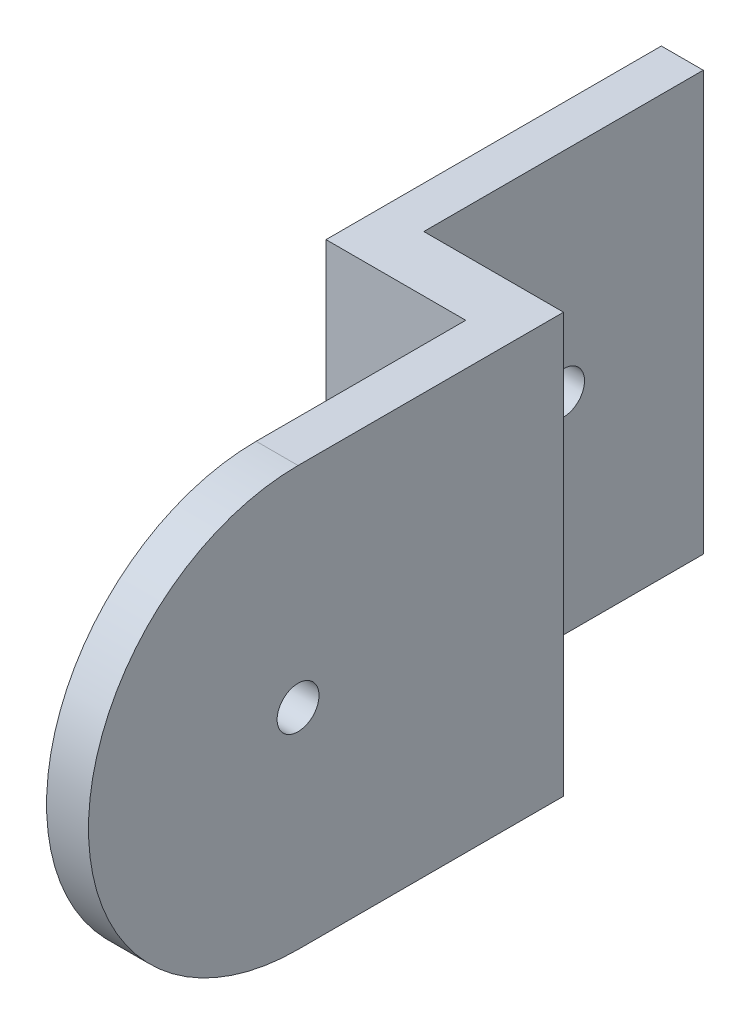
SolidWorks part; units mm, degrees
ref_plane "前视基准面" through (0, 0, 0) normal (0, 0, 1) x (1, 0, 0)
ref_plane "上视基准面" through (0, 0, 0) normal (0, 1, 0) x (1, 0, 0)
ref_plane "右视基准面" through (0, 0, 0) normal (1, 0, 0) x (0, 0, -1)
sketch "草图1" plane through (0, 0, 0) normal (0, 0, 1) x (1, 0, 0)
  line L1 (0, 0) -> (81, 0)
  line L2 (0, 0) -> (0, -30)
  line L3 (0, -30) -> (81, -30)
  line L4 (81, 0) -> (81, -30)
  dimension "D1" = 81
  dimension "D2" = 30
extrude "凸台-拉伸1" add sketch "草图1" along normal blind 4
sketch "草图2" plane through (0, 0, 0) normal (0, 0, -1) x (-1, 0, 0)
  line L0 (0, -30) -> (-81, -30) construction
  line L1 (0, 0) -> (-3, 0)
  line L2 (0, 0) -> (0, -30)
  line L3 (0, -30) -> (-3, -30)
  line L4 (-3, 0) -> (-3, -30)
  line L6 (-81, 0) -> (-78, 0)
  line L7 (-81, 0) -> (-81, -30)
  line L8 (-81, -30) -> (-78, -30)
  line L9 (-78, 0) -> (-78, -30)
  dimension "D1" = 3
  dimension "D2" = 3
extrude "凸台-拉伸2" add sketch "草图2" along normal blind 20
sketch "草图3" plane through (0, 0, 0) normal (-1, 0, 0) x (0, 0, 1)
  line L0 (0, 0) -> (0, -30) construction
  line L1 (4, -30) -> (-20, -30) construction
  line L2 (0, -15) -> (-20, -15) construction
  line L3 (-20, -30) -> (-20, 0) construction
  circle A0 centre (-10, -15) radius 1.5
  dimension "D1" = 3
extrude "切除-拉伸1" cut sketch "草图3" against normal up to surface (81 mm away) up to face at (81, -15, -8)
sketch "草图4" plane through (0, 0, 4) normal (0, 0, 1) x (1, 0, 0)
  line L0 (40.5, 0) -> (40.5, -30) construction
  line L1 (81, 0) -> (0, 0) construction
  line L2 (0, -30) -> (81, -30) construction
  line L3 (13, -30) -> (10, -30)
  line L4 (13, -30) -> (68, -30)
  line L5 (13, -30) -> (13, 0)
  line L6 (13, 0) -> (68, 0)
  line L7 (68, -30) -> (68, 0)
  line L8 (13, -30) -> (68, 0) construction
  line L9 (13, 0) -> (68, -30) construction
  line L10 (68, 0) -> (71, 0)
  line L11 (68, 0) -> (68, -30)
  line L12 (68, -30) -> (71, -30)
  line L13 (71, 0) -> (71, -30)
  line L14 (10, 0) -> (10, -30)
  line L15 (13, 0) -> (10, 0)
  line L16 (13, 0) -> (13, -30)
  point P6 (40.5, -15)
  line M11 (0, -30) -> (81, -30)
  line M13 (81, 0) -> (0, 0)
  dimension "D1" = 55
  dimension "D2" = 3
extrude "凸台-拉伸3" add sketch "草图4" along normal blind 30 contours L14 L5 M13 M11 | L13 L7 M13 M11
sketch "草图7" plane through (10, 0, 0) normal (-1, 0, 0) x (0, 0, 1)
  line L0 (19, 0) -> (19, -30) construction
  line L1 (4, 0) -> (4, -30) construction
  line L2 (34, 0) -> (4, 0) construction
  line L3 (34, -30) -> (4, -30) construction
  line L8 (4, 0) -> (4, -30)
  line L9 (4, -30) -> (34, -30)
  line L10 (34, -30) -> (34, 0)
  line L11 (34, 0) -> (4, 0)
  line L12 (4, 0) -> (4, -30)
  line L13 (4, -30) -> (34, -30)
  line L14 (34, -30) -> (34, 0)
  line L15 (34, 0) -> (4, 0)
  arc A0 (19, 0) -> (19, -30) centre (19, -15) cw
  line M8 (34, -30) -> (34, 0)
  line M9 (34, 0) -> (4, 0)
  dimension "D1" = 0
extrude "切除-拉伸2" cut sketch "草图7" against normal up to surface (61 mm away) contours A0 L14 M9 | A0 L13 M8 up to face at (71, -15, 19)
sketch "草图8" plane through (10, 0, 0) normal (-1, 0, 0) x (0, 0, 1)
  line L0 (19, 0) -> (19, -15) construction
  arc A0 (19, -30) -> (19, 0) centre (19, -15) ccw construction
  circle A1 centre (19, -15) radius 1.5
  dimension "D1" = 3
extrude "切除-拉伸3" cut sketch "草图8" against normal up to surface (61 mm away) up to face at (71, -15, 15.25)
sketch "草图9" plane through (0, -30, 0) normal (0, -1, 0) x (1, 0, 0)
  line L0 (13, 19) -> (13, 34) construction
  line L1 (13, 34) -> (81, 34)
  line L2 (13, 34) -> (13, -20)
  line L3 (13, -20) -> (81, -20)
  line L4 (81, 34) -> (81, -20)
extrude "切除-拉伸4" cut sketch "草图9" against normal up to surface (30 mm away) up to face at (40.5, 0, 1.25)
